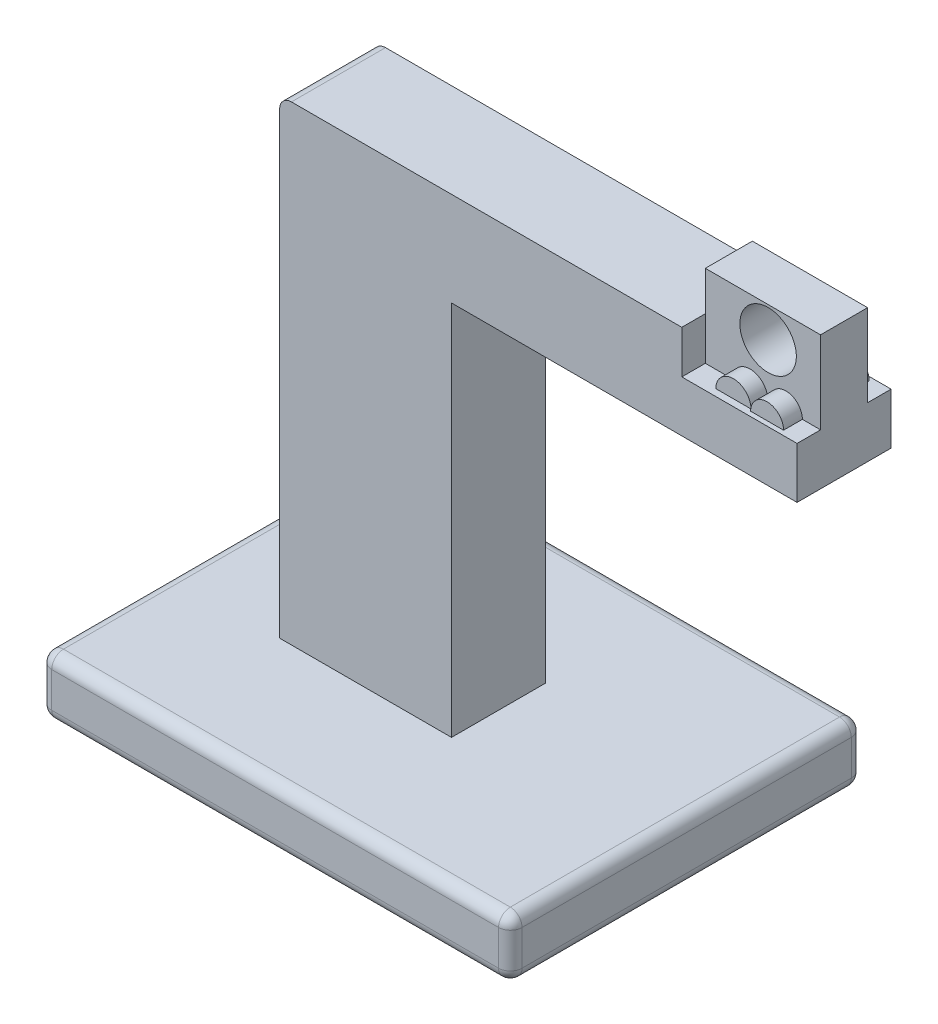
SolidWorks part; units mm, degrees
material "Commercially Pure CP-Ti UNS R50400 (SS)"
ref_plane "Front Plane" through (0, 0, 0) normal (0, 0, 1) x (1, 0, 0)
ref_plane "Top Plane" through (0, 0, 0) normal (0, 1, 0) x (1, 0, 0)
ref_plane "Right Plane" through (0, 0, 0) normal (1, 0, 0) x (0, 0, -1)
sketch "Sketch1" plane through (0, 0, 0) normal (0, 1, 0) x (1, 0, 0)
  line L1 (0, 0) -> (508, 0)
  line L2 (0, 0) -> (0, 381)
  line L3 (0, 381) -> (508, 381)
  line L4 (508, 0) -> (508, 381)
  dimension "D1" = 381
  dimension "D2" = 508
extrude "Boss-Extrude1" add sketch "Sketch1" along normal blind 63.5
fillet "Fillet4" radius 12.7 1 edges at (508, 31.75, 0)
fillet "Fillet5" radius 12.7 1 edges at (508, 31.75, -381)
fillet "Fillet6" radius 12.7 1 edges at (0, 31.75, -381)
fillet "Fillet7" radius 12.7 1 edges at (0, 31.75, 0)
fillet "Fillet8" radius 12.7 8 edges at (508, 0, -190.5) (504.2803, 0, -3.7197) (254, 0, -381) (504.2803, 0, -377.2803) (0, 0, -190.5) (3.7197, 0, -377.2803) (254, 0, 0) (3.7197, 0, -3.7197)
fillet "Fillet9" radius 12.7 8 edges at (508, 63.5, -190.5) (504.2803, 63.5, -3.7197) (254, 63.5, -381) (504.2803, 63.5, -377.2803) (0, 63.5, -190.5) (3.7197, 63.5, -377.2803) (254, 63.5, 0) (3.7197, 63.5, -3.7197)
sketch "Sketch2" plane through (0, 63.5, 0) normal (0, 1, 0) x (1, 0, 0)
  line L0 (495.3, 368.3) -> (12.7, 368.3) construction
  line L1 (119.2174, 241.3) -> (304.8, 241.3)
  line L2 (119.2174, 241.3) -> (119.2174, 139.7)
  line L3 (119.2174, 139.7) -> (304.8, 139.7)
  line L4 (304.8, 241.3) -> (304.8, 139.7)
  line L5 (12.7, 12.7) -> (495.3, 12.7) construction
  line L6 (495.3, 12.7) -> (495.3, 368.3) construction
  dimension "D1" = 127
  dimension "D2" = 101.6
  dimension "D3" = 127
  dimension "D4" = 190.5
extrude "Boss-Extrude2" add sketch "Sketch2" along normal blind 406.4
ref_plane "Plane16" through (119.2174, 0, 0) normal (-1, 0, 0) x (0, 0, 1)
sketch "Sketch26" plane through (119.2174, 0, 0) normal (-1, 0, 0) x (0, 0, 1)
  line L1 (-139.7, 469.9) -> (-241.3, 469.9)
  line L2 (-139.7, 469.9) -> (-139.7, 571.5)
  line L3 (-139.7, 571.5) -> (-241.3, 571.5)
  line L4 (-241.3, 469.9) -> (-241.3, 571.5)
  dimension "D1" = 101.6
  dimension "D2" = 0
extrude "Boss-Extrude16" add sketch "Sketch26" against normal blind 558.8
ref_plane "Plane21" through (680.5574, 0, 0) normal (1, 0, 0) x (0, 0, -1)
sketch "Sketch28" plane through (680.5574, 0, 0) normal (1, 0, 0) x (0, 0, -1)
  line L1 (139.664, 575.8877) -> (241.5139, 575.8877)
  line L2 (139.664, 575.8877) -> (139.664, 525.0877)
  line L3 (139.664, 525.0877) -> (241.5139, 525.0877)
  line L4 (241.5139, 575.8877) -> (241.5139, 525.0877)
  dimension "D1" = 50.8
extrude "Cut-Extrude8" cut sketch "Sketch28" against normal blind 127 contours L2 L1 L4 L3
ref_plane "Plane23" through (0, 525.0877, 0) normal (0, 1, 0) x (1, 0, 0)
sketch "Sketch29" plane through (0, 525.0877, 0) normal (0, 1, 0) x (1, 0, 0)
  line L0 (678.0174, 241.3) -> (678.0174, 139.7) construction
  line L1 (678.0174, 165.1) -> (553.5574, 165.1)
  line L2 (678.0174, 165.1) -> (678.0174, 215.9)
  line L3 (678.0174, 215.9) -> (553.5574, 215.9)
  line L4 (553.5574, 165.1) -> (553.5574, 215.9)
  line L5 (553.5574, 139.7) -> (553.5574, 241.3) construction
  line L6 (553.5574, 241.3) -> (678.0174, 241.3) construction
  line L7 (678.0174, 139.7) -> (553.5574, 139.7) construction
  dimension "D1" = 25.4
  dimension "D2" = 25.4
extrude "Boss-Extrude18" add sketch "Sketch29" along normal blind 88.9
fillet "Fillet10" radius 12.7 1 edges at (119.2174, 571.5, -190.5)
ref_plane "Plane24" through (0, 0, -218.44) normal (0, 0, -1) x (-1, 0, 0)
sketch "Sketch31" plane through (0, 0, -218.44) normal (0, 0, -1) x (-1, 0, 0)
  circle A0 centre (-640.5809, 525.0419) radius 17.78
extrude "Boss-Extrude21" add sketch "Sketch31" against normal blind 73.66 and the other way blind 18.796
sketch "Sketch32" plane through (0, 0, -218.44) normal (0, 0, -1) x (-1, 0, 0)
  circle A0 centre (-601.9061, 524.9039) radius 19.05
extrude "Boss-Extrude22" add sketch "Sketch32" against normal blind 71.374 and the other way blind 14.986
sketch "Sketch33" plane through (0, 0, -218.44) normal (0, 0, -1) x (-1, 0, 0)
  circle A0 centre (-621.3465, 580.7907) radius 30.48
extrude "Cut-Extrude10" cut sketch "Sketch33" against normal blind 71.374
scale "Scale1" scale about centroid uniform scaling yes scale factor 1.5
